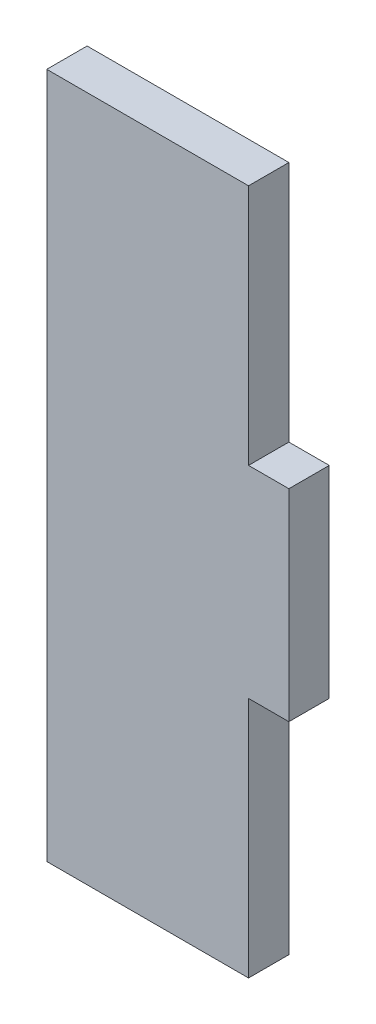
SolidWorks part; units mm, degrees
ref_plane "Front Plane" through (0, 0, 0) normal (0, 0, 1) x (1, 0, 0)
ref_plane "Top Plane" through (0, 0, 0) normal (0, 1, 0) x (1, 0, 0)
ref_plane "Right Plane" through (0, 0, 0) normal (1, 0, 0) x (0, 0, -1)
sketch "Sketch1" plane through (0, 0, 0) normal (0, 0, 1) x (1, 0, 0)
  line L0 (0, 0) -> (0, 51)
  line L1 (0, 51) -> (15, 51)
  line L2 (15, 51) -> (15, 33)
  line L3 (15, 33) -> (18, 33)
  line L4 (18, 33) -> (18, 18)
  line L5 (18, 18) -> (15, 18)
  line L6 (15, 18) -> (15, 0)
  line L7 (15, 0) -> (0, 0)
  dimension "D1" = 15
  dimension "D2" = 51
  dimension "D3" = 15
  dimension "D4" = 3
extrude "Boss-Extrude1" add sketch "Sketch1" along normal blind 3
